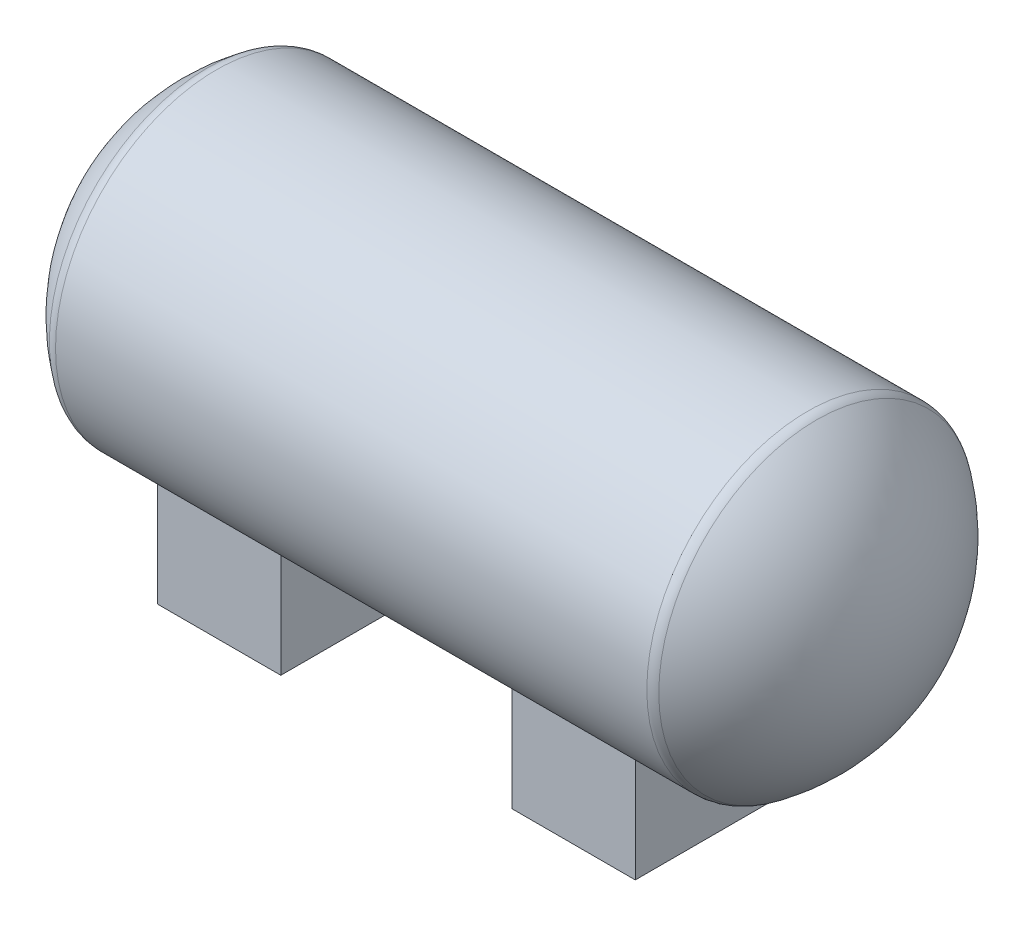
SolidWorks part; units mm, degrees
ref_plane "正面" through (0, 0, 0) normal (0, 0, 1) x (1, 0, 0)
ref_plane "平面" through (0, 0, 0) normal (0, 1, 0) x (1, 0, 0)
ref_plane "右側面" through (0, 0, 0) normal (1, 0, 0) x (0, 0, -1)
sketch "ｽｹｯﾁ1" plane through (0, 0, 0) normal (0, 0, 1) x (1, 0, 0)
  line L0 (-19.5, 0) -> (19.5, 0) construction
  line L1 (-19.5, 10.4355) -> (19.5, 10.4355)
  line L2 (-25, 0) -> (25, 0)
  arc A0 (-19.5, 10.4355) -> (-25, 0) centre (-12.35, 0) ccw
  arc A1 (19.5, 10.4355) -> (25, 0) centre (12.35, 0) cw
  dimension "D2" = 12.65
  dimension "D3" = 12.65
  dimension "D1" = 39
  dimension "D4" = 39
  dimension "D5" = 5.5
  dimension "D6" = 5.5
revolve "回転2" add sketch "ｽｹｯﾁ1" angle 360 about L0
sketch "ｽｹｯﾁ3" plane through (0, 0, 0) normal (0, 1, 0) x (1, 0, 0)
  line L0 (-25, 0) -> (25, 0) construction
  line L1 (-19.5, -10.4355) -> (-19.5, 10.4355) construction
  line L2 (-7.5, -7.5) -> (-15.5, -7.5)
  line L3 (-7.5, -7.5) -> (-7.5, 7.5)
  line L4 (-7.5, 7.5) -> (-15.5, 7.5)
  line L5 (-15.5, -7.5) -> (-15.5, 7.5)
  line L6 (-7.5, -7.5) -> (-15.5, 7.5) construction
  line L7 (-7.5, 7.5) -> (-15.5, -7.5) construction
  line L8 (15.5, -7.5) -> (7.5, -7.5)
  line L9 (15.5, -7.5) -> (15.5, 7.5)
  line L10 (15.5, 7.5) -> (7.5, 7.5)
  line L11 (7.5, -7.5) -> (7.5, 7.5)
  line L12 (15.5, -7.5) -> (7.5, 7.5) construction
  line L13 (15.5, 7.5) -> (7.5, -7.5) construction
  line L14 (19.5, -10.4355) -> (19.5, 10.4355) construction
  arc A0 (-19.5, 10.4355) -> (-19.5, -10.4355) centre (-12.35, 0) ccw construction
  arc A1 (19.5, -10.4355) -> (19.5, 10.4355) centre (12.35, 0) ccw construction
  point P8 (-11.5, 0)
  point P13 (11.5, 0)
  dimension "D1" = 4
  dimension "D2" = 4
  dimension "D3" = 15
  dimension "D4" = 15
  dimension "D5" = 8
  dimension "D6" = 8
extrude "ﾎﾞｽ - 押し出し1" add sketch "ｽｹｯﾁ3" against normal blind 14
sketch "ｽｹｯﾁ4" plane through (0, -14, 0) normal (0, -1, 0) x (-1, 0, 0)
  line L0 (-11.5, 7.5) -> (-11.5, -7.5) construction
  line L1 (-15.5, 7.5) -> (-7.5, 7.5) construction
  line L2 (-7.5, -7.5) -> (-15.5, -7.5) construction
  line L3 (-11.5, -7.5) -> (11.5, 7.5) construction
  line L4 (7.5, 7.5) -> (15.5, 7.5) construction
  line L5 (11.5, 7.5) -> (11.5, -7.5) construction
  line L6 (15.5, -7.5) -> (7.5, -7.5) construction
  line L7 (11.5, -7.5) -> (-11.5, 7.5) construction
  circle A0 centre (-11.5, 0) radius 1.5
  circle A1 centre (11.5, 0) radius 1.5
  dimension "D1" = 3
  dimension "D2" = 3
extrude "ｶｯﾄ - 押し出し1" cut sketch "ｽｹｯﾁ4" against normal blind 10
fillet "ﾌｨﾚｯﾄ1" radius 1 2 edges at (-19.5, 0, 10.4355) (19.5, 0, 10.4355)
